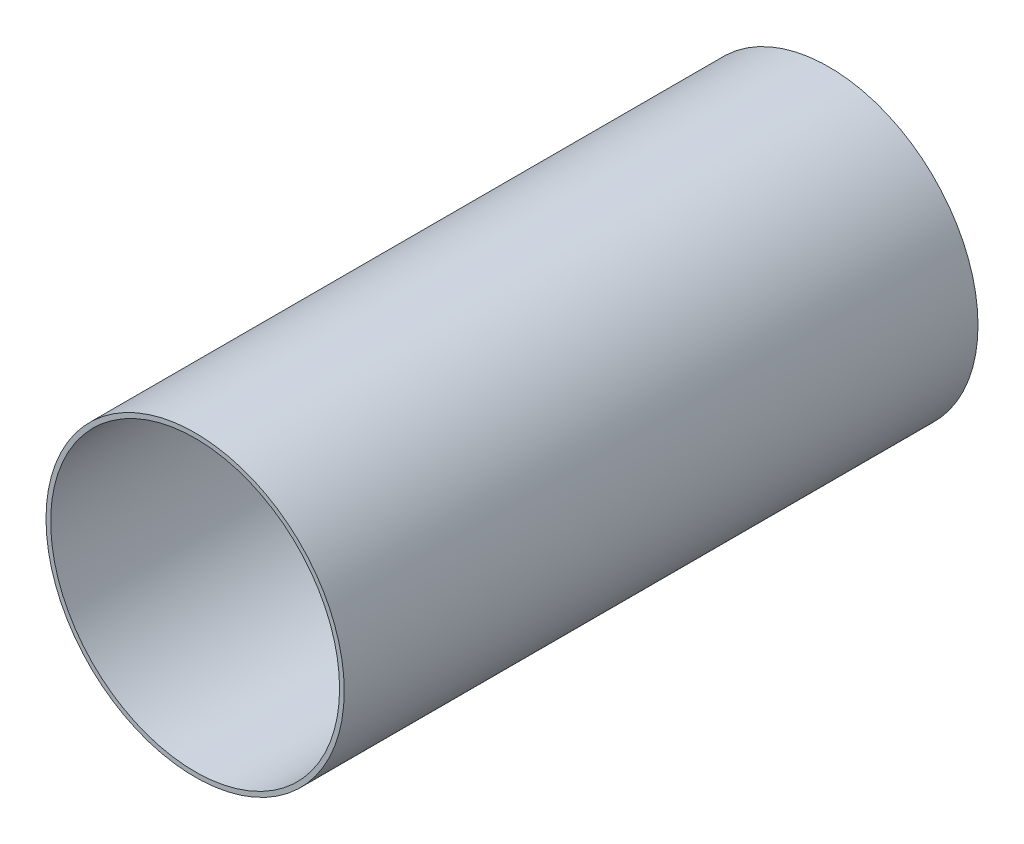
SolidWorks part; units mm, degrees
material "PC High Viscosity"
ref_plane "Front Plane" through (0, 0, 0) normal (0, 0, 1) x (1, 0, 0)
ref_plane "Top Plane" through (0, 0, 0) normal (0, 1, 0) x (1, 0, 0)
ref_plane "Right Plane" through (0, 0, 0) normal (1, 0, 0) x (0, 0, -1)
sketch "Sketch1" plane through (0, 0, 0) normal (0, 0, 1) x (1, 0, 0)
  circle A0 centre (0, 0) radius 98.425
  circle A1 centre (0, 0) radius 101.6
  dimension "D1" = 196.85
  dimension "D2" = 203.2
extrude "Boss-Extrude1" add sketch "Sketch1" along normal blind 431.8
